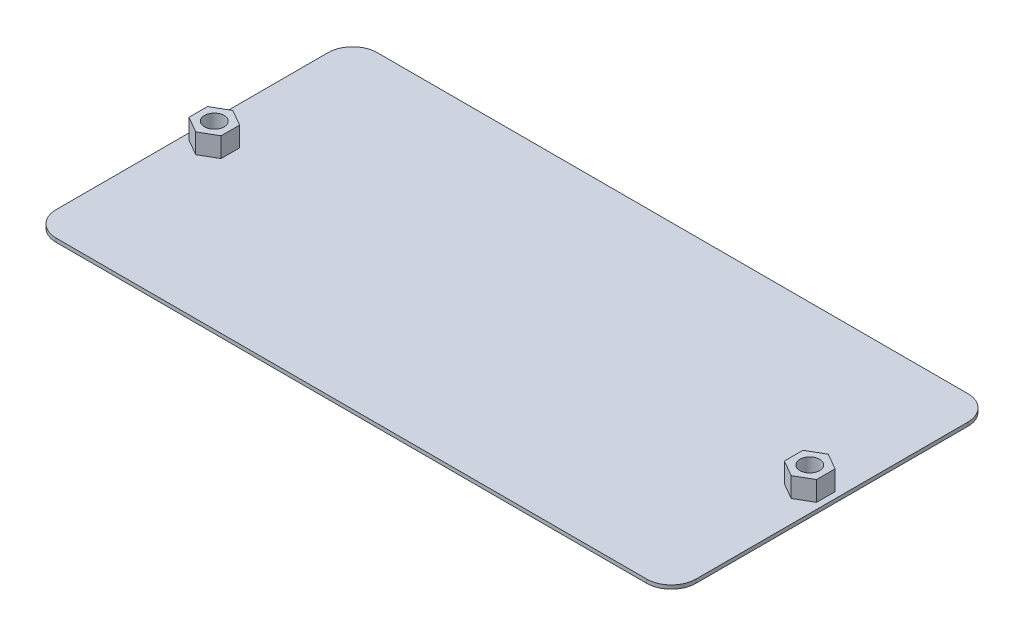
SolidWorks part; units mm, degrees
material "C40 or 38NiCrMo4"
ref_plane "Piano frontale" through (0, 0, 0) normal (0, 0, 1) x (1, 0, 0)
ref_plane "Piano superiore" through (0, 0, 0) normal (0, 1, 0) x (1, 0, 0)
ref_plane "Piano destro" through (0, 0, 0) normal (1, 0, 0) x (0, 0, -1)
sketch "Schizzo1" plane through (0, 0, 0) normal (0, 1, 0) x (1, 0, 0)
  line L0 (-1000, 65) -> (49000, 65) construction
  line L1 (10, 0) -> (249, 0)
  line L2 (0, 10) -> (0, 120)
  line L3 (10, 130) -> (249, 130)
  line L4 (259, 10) -> (259, 120)
  line L5 (129.5, -870) -> (129.5, 49130) construction
  arc A0 (249, 130) -> (259, 120) centre (249, 120) cw
  arc A1 (249, 0) -> (259, 10) centre (249, 10) ccw
  arc A2 (10, 0) -> (0, 10) centre (10, 10) cw
  arc A3 (0, 120) -> (10, 130) centre (10, 120) cw
  circle A4 centre (9, 65) radius 4.5
  circle A5 centre (250, 65) radius 4.5
  point P9 (259, 0)
  point P12 (0, 0)
  point P15 (0, 130)
  point P19 (0, 65)
  point P22 (129.5, 130)
  dimension "D3" = 10
  dimension "D5" = 9
  dimension "D1" = 259
  dimension "D2" = 130
  dimension "D4" = 120.5
extrude "Estrusione-Estrusione1" add sketch "Schizzo1" along normal blind 1.5
sketch "Schizzo2" plane through (0, 1.5, 0) normal (0, 1, 0) x (-1, 0, 0)
  line L0 (0, -120) -> (0, -10) construction
  line L1 (-9, -57.4944) -> (-15.5, -61.2472)
  line L2 (-15.5, -61.2472) -> (-15.5, -68.7528)
  line L3 (-15.5, -68.7528) -> (-9, -72.5056)
  line L4 (-9, -72.5056) -> (-2.5, -68.7528)
  line L5 (-2.5, -68.7528) -> (-2.5, -61.2472)
  line L6 (-2.5, -61.2472) -> (-9, -57.4944)
  line L7 (-129.5, -1130) -> (-129.5, 48870) construction
  line L8 (-249, -130) -> (-10, -130) construction
  line L9 (-256.5, -61.2472) -> (-250, -57.4944)
  line L10 (-256.5, -68.7528) -> (-256.5, -61.2472)
  line L11 (-250, -72.5056) -> (-256.5, -68.7528)
  line L12 (-243.5, -68.7528) -> (-250, -72.5056)
  line L13 (-243.5, -61.2472) -> (-243.5, -68.7528)
  line L14 (-250, -57.4944) -> (-243.5, -61.2472)
  circle A0 centre (-9, -65) radius 6.5 construction
  circle A1 centre (-250, -65) radius 6.5 construction
  circle A2 centre (-250, -65) radius 4
  circle A3 centre (-9, -65) radius 4
  point P16 (-129.5, -130)
  dimension "D2" = 8
  dimension "D1" = 13
extrude "Estrusione-Estrusione2" add sketch "Schizzo2" along normal blind 8
